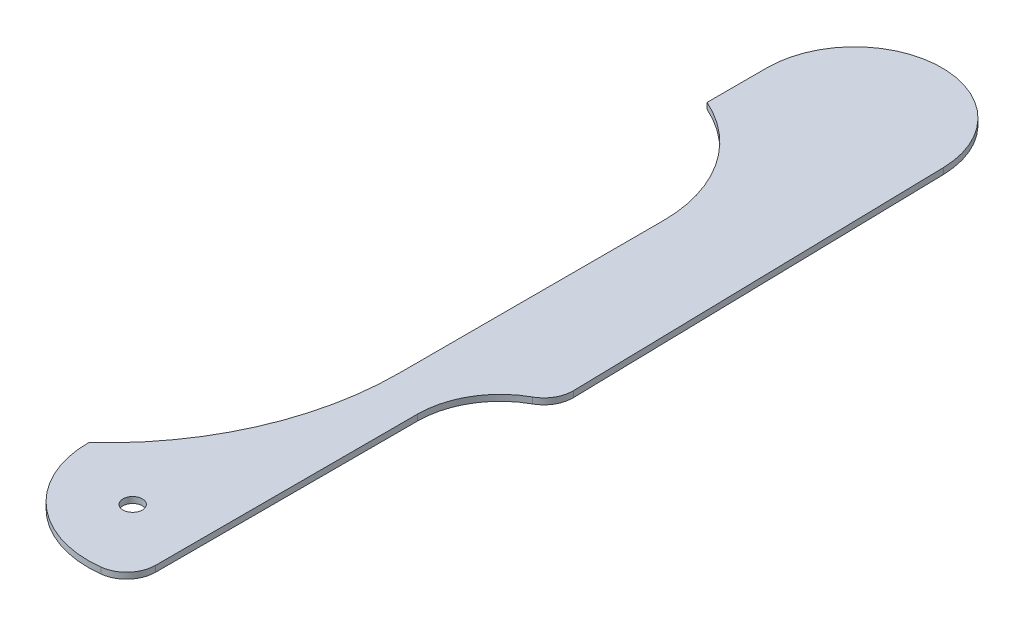
SolidWorks part; units mm, degrees
ref_plane "Front Plane" through (0, 0, 0) normal (0, 0, 1) x (1, 0, 0)
ref_plane "Top Plane" through (0, 0, 0) normal (0, 1, 0) x (1, 0, 0)
ref_plane "Right Plane" through (0, 0, 0) normal (1, 0, 0) x (0, 0, -1)
sketch "Sketch1" plane through (0, 0, 0) normal (0, 1, 0) x (1, 0, 0)
  line L0 (8.9979, 0.1963) -> (9.8488, -38.8037)
  line L1 (0, 33.641) -> (0, -90.1403) construction
  line L2 (3.9, -48.941) -> (3.9, -75.941)
  line L4 (-0.7, -46.2371) -> (-0.7, -18.9871)
  line L5 (-9, -6.2) -> (-9, 0)
  arc A0 (-9, 0) -> (8.9979, 0.1963) centre (0, 0) cw
  arc A1 (9.8488, -38.8037) -> (8.2975, -41.4966) centre (6.8496, -38.8691) cw
  arc A2 (8.2975, -41.4966) -> (3.9, -48.941) centre (12.4, -48.941) ccw
  arc A3 (1.26, -78.9193) -> (-10.4997, -68.417) centre (0, -68.4952) cw
  arc A5 (-0.7, -18.9871) -> (-9, -6.2) centre (-14.7, -18.9871) ccw
  arc A6 (-10.4997, -68.417) -> (-0.7, -46.2371) centre (-30.7, -46.2371) ccw
  arc A7 (3.9, -75.941) -> (1.26, -78.9193) centre (0.9, -75.941) cw
  point P22 (1.5018, -75.8343)
  dimension "D1" = 9
  dimension "D3" = 3
  dimension "D4" = 8.5
  dimension "D7" = 3
  dimension "D8" = 10.5
  dimension "D9" = 30
  dimension "D12" = 14
  dimension "D2" = 39
  dimension "D5" = 27
  dimension "D6" = 3.9
  dimension "D10" = 0.7
  dimension "D11" = 27.25
  dimension "D13" = 6.2
  dimension "D14" = 1.25
  dimension "D15" = 27
extrude "Boss-Extrude1" add sketch "Sketch1" along normal blind 0.625
sketch "Sketch2" plane through (0, 0.625, 0) normal (0, 1, 0) x (1, 0, 0)
  line L0 (3.9, -75.941) -> (3.9, -48.941) construction
  circle A0 centre (-2.7164, -71.6952) radius 1
  point P7 (-23.8822, -60.1285)
  dimension "D1" = 2
  dimension "D2" = 5.6164
extrude "Cut-Extrude1" cut sketch "Sketch2" against normal blind 2
scale "Scale1" scale about centroid uniform scaling yes scale factor 0.6
